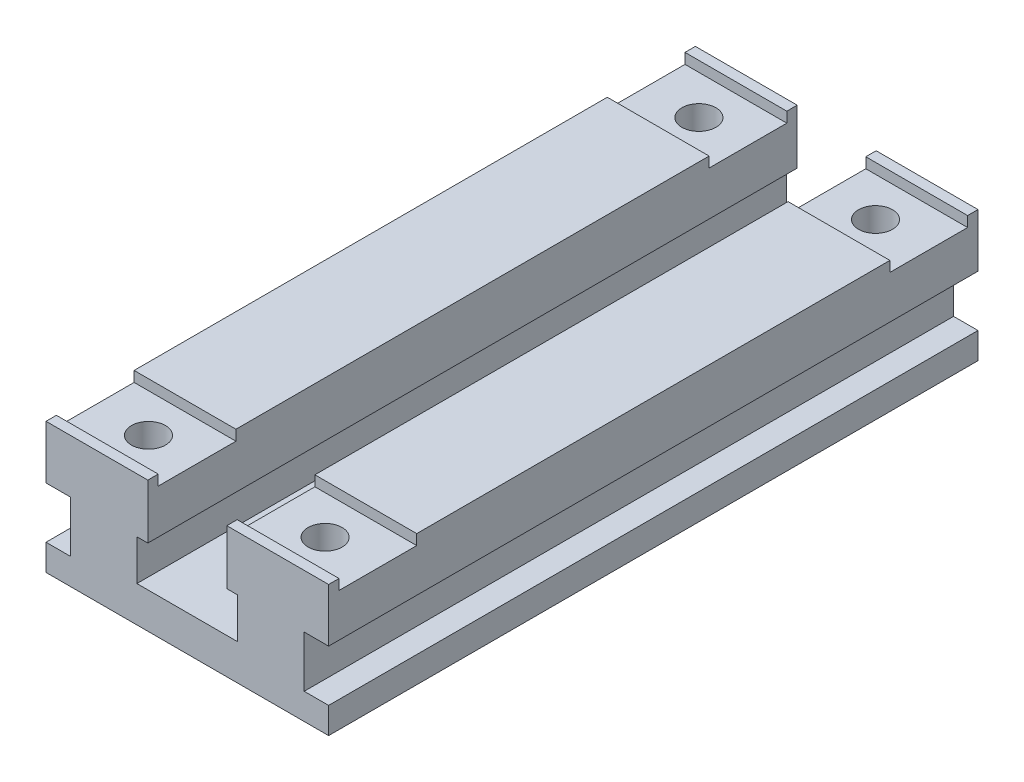
SolidWorks part; units mm, degrees
ref_plane "Front" through (0, 0, 0) normal (0, 0, 1) x (1, 0, 0)
ref_plane "Top" through (0, 0, 0) normal (0, 1, 0) x (1, 0, 0)
ref_plane "Right" through (0, 0, 0) normal (1, 0, 0) x (0, 0, -1)
sketch "Sketch1" plane through (0, 0, 0) normal (0, 0, 1) x (1, 0, 0)
  line L0 (-16.6381, 6.4008) -> (-16.6381, 0)
  line L1 (-16.6381, 32.004) -> (52.4499, 32.004)
  line L2 (-16.6381, 32.004) -> (-16.6381, 18.9484)
  line L3 (-16.6381, 0) -> (52.4499, 0)
  line L4 (52.4499, 32.004) -> (52.4499, 18.9484)
  line L5 (-16.6381, 18.9484) -> (-10.6691, 18.9484)
  line L6 (17.9059, 32.004) -> (17.9059, -2.6271) construction
  line L7 (-16.6381, 6.4008) -> (-10.6691, 6.4008)
  line L8 (-10.6691, 18.9484) -> (-10.6691, 6.4008)
  line L9 (52.4499, 6.4008) -> (46.4809, 6.4008)
  line L10 (46.4809, 18.9484) -> (46.4809, 6.4008)
  line L11 (52.4499, 18.9484) -> (46.4809, 18.9484)
  line L12 (52.4499, 6.4008) -> (52.4499, 0)
extrude "Extrude1" add sketch "Sketch1" along normal blind 158.75
sketch "Sketch2" plane through (-16.6381, 0, 0) normal (-1, 0, 0) x (0, 0, 1)
  line L0 (158.75, 32.004) -> (0, 32.004) construction
  line L1 (2.54, 39.0305) -> (21.5392, 39.0305)
  line L2 (2.54, 39.0305) -> (2.54, 29.464)
  line L3 (2.54, 29.464) -> (21.5392, 29.464)
  line L4 (21.5392, 39.0305) -> (21.5392, 29.464)
  line L5 (79.375, 32.004) -> (79.375, 13.781) construction
  line L6 (156.21, 39.0305) -> (156.21, 29.464)
  line L7 (156.21, 39.0305) -> (137.2108, 39.0305)
  line L8 (137.2108, 39.0305) -> (137.2108, 29.464)
  line L9 (156.21, 29.464) -> (137.2108, 29.464)
extrude "Cut-Extrude1" cut sketch "Sketch2" against normal blind 158.75
sketch "Sketch3" plane through (0, 29.464, 0) normal (0, 1, 0) x (-1, 0, 0)
  line L0 (-52.4499, 0) -> (16.6381, 0) construction
  line L1 (16.6381, 79.375) -> (-89.128, 79.375) construction
  line L2 (16.6381, 137.2108) -> (16.6381, 21.5392) construction
  line L3 (-17.9059, 158.75) -> (-17.9059, -10.1399) construction
  line L4 (16.6381, 158.75) -> (-52.4499, 158.75) construction
  line L6 (-52.4499, 158.75) -> (16.6381, 158.75) construction
  circle A0 centre (3.6841, 12.0968) radius 4.1593
  circle A1 centre (-39.4959, 12.0968) radius 4.1593
  circle A2 centre (-39.4959, 146.6533) radius 4.1593
  circle A3 centre (3.6841, 146.6533) radius 4.1592
extrude "Cut-Extrude2" cut sketch "Sketch3" against normal blind 158.75
sketch "Sketch4" plane through (0, 0, 0) normal (0, -1, 0) x (1, 0, 0)
  line L0 (-16.6381, 79.375) -> (59.888, 79.375) construction
  line L1 (-16.6381, 158.75) -> (-16.6381, 0) construction
  circle A0 centre (-3.6841, 146.6533) radius 6.2548
  circle A1 centre (39.4959, 146.6533) radius 6.2548
  circle A2 centre (-3.6841, 146.6533) radius 4.1592 construction
  circle A3 centre (39.4959, 146.6533) radius 4.1593 construction
  circle A4 centre (39.4959, 12.0967) radius 6.2547
  circle A5 centre (-3.6841, 12.0967) radius 6.2547
extrude "Cut-Extrude3" cut sketch "Sketch4" against normal blind 8.8392
sketch "Sketch5" plane through (0, 0, 0) normal (0, 0, 1) x (1, 0, 0)
  line L0 (17.9059, 42.5669) -> (17.9059, -5.5317) construction
  line L1 (52.4499, 32.004) -> (-16.6381, 32.004) construction
  line L2 (8.2539, 18.669) -> (5.5869, 18.669)
  line L3 (8.2539, 32.004) -> (27.5579, 32.004)
  line L4 (8.2539, 32.004) -> (8.2539, 18.669)
  line L7 (5.5869, 18.669) -> (5.5869, 8.763)
  line L9 (30.2249, 8.763) -> (5.5869, 8.763)
  line L10 (30.2249, 18.669) -> (30.2249, 8.763)
  line L11 (27.5579, 32.004) -> (27.5579, 18.669)
  line L12 (27.5579, 18.669) -> (30.2249, 18.669)
  point P4 (17.9059, 32.004)
  point P6 (17.9059, 32.004)
  point P7 (17.9059, 8.763)
extrude "Extrude2" cut sketch "Sketch5" along normal up to next
ref_plane "Plane1" through (0, 0, 158.75) normal (0, 0, 1) x (1, 0, 0)
sketch "Sketch9" plane through (0, 0, 158.75) normal (0, 0, 1) x (1, 0, 0)
  line L0 (-2.0428, 2.4304) -> (38.395, 2.4304)
sketch "Sketch10" plane through (0, 0, 158.75) normal (0, 0, 1) x (1, 0, 0)
  text T0 "92-197REV1-XX"
extrude "Extrude3" [suppressed] cut sketch "Sketch10" against normal blind 0.508
